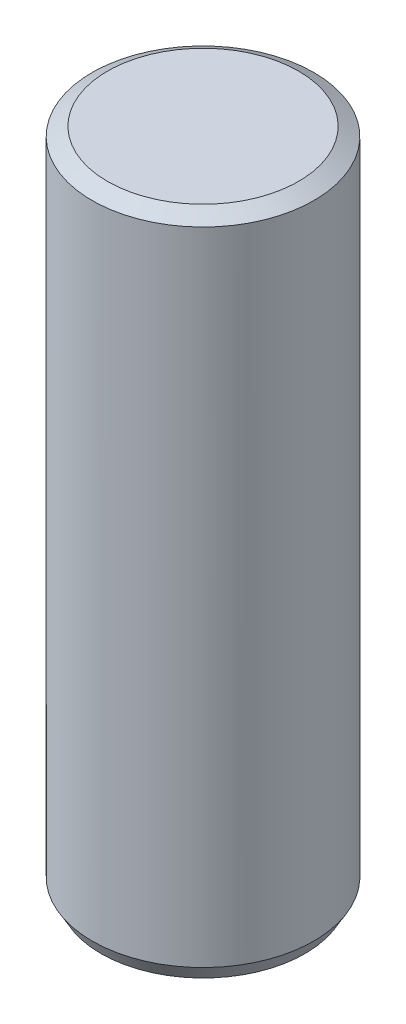
SolidWorks part; units mm, degrees
material "Alloy Steel"
ref_plane "Front Plane" through (0, 0, 0) normal (0, 0, 1) x (1, 0, 0)
ref_plane "Top Plane" through (0, 0, 0) normal (0, 1, 0) x (1, 0, 0)
ref_plane "Right Plane" through (0, 0, 0) normal (1, 0, 0) x (0, 0, -1)
sketch "Sketch1" plane through (0, 0, 0) normal (0, 1, 0) x (1, 0, 0)
  circle A0 centre (0, 0) radius 3.175
  dimension "D1" = 6.35
extrude "Boss-Extrude1" add sketch "Sketch1" along normal blind 19.05
chamfer "Chamfer1" distance 0.254 angle 60 2 edges at (0, 0, 3.175) (0, 19.05, 3.175)
